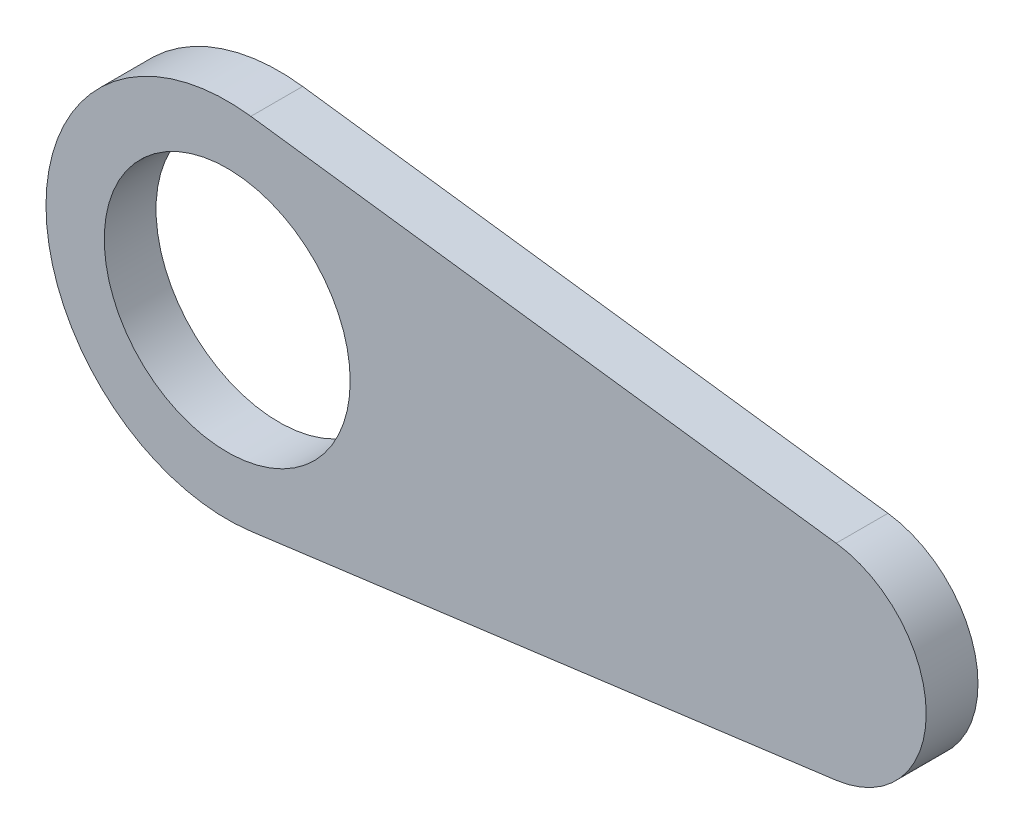
SolidWorks part; units mm, degrees
ref_plane "Front Plane" through (0, 0, 0) normal (0, 0, 1) x (1, 0, 0)
ref_plane "Top Plane" through (0, 0, 0) normal (0, 1, 0) x (1, 0, 0)
ref_plane "Right Plane" through (0, 0, 0) normal (1, 0, 0) x (0, 0, -1)
sketch "Sketch5" plane through (0, 0, 0) normal (0, 0, 1) x (1, 0, 0)
  line L0 (0.913, 6.9402) -> (23.5217, 3.9658)
  line L1 (0.913, -6.9402) -> (23.5217, -3.9658)
  circle A0 centre (0, 0) radius 7
  circle A1 centre (23, 0) radius 4
  circle A2 centre (0, 0) radius 4.75
  dimension "D1" = 14
  dimension "D2" = 8
  dimension "D4" = 9.5
  dimension "D3" = 23
extrude "Boss-Extrude1" add sketch "Sketch5" along normal blind 2 contours A0 | A1 L0 A0 L1 | A1
